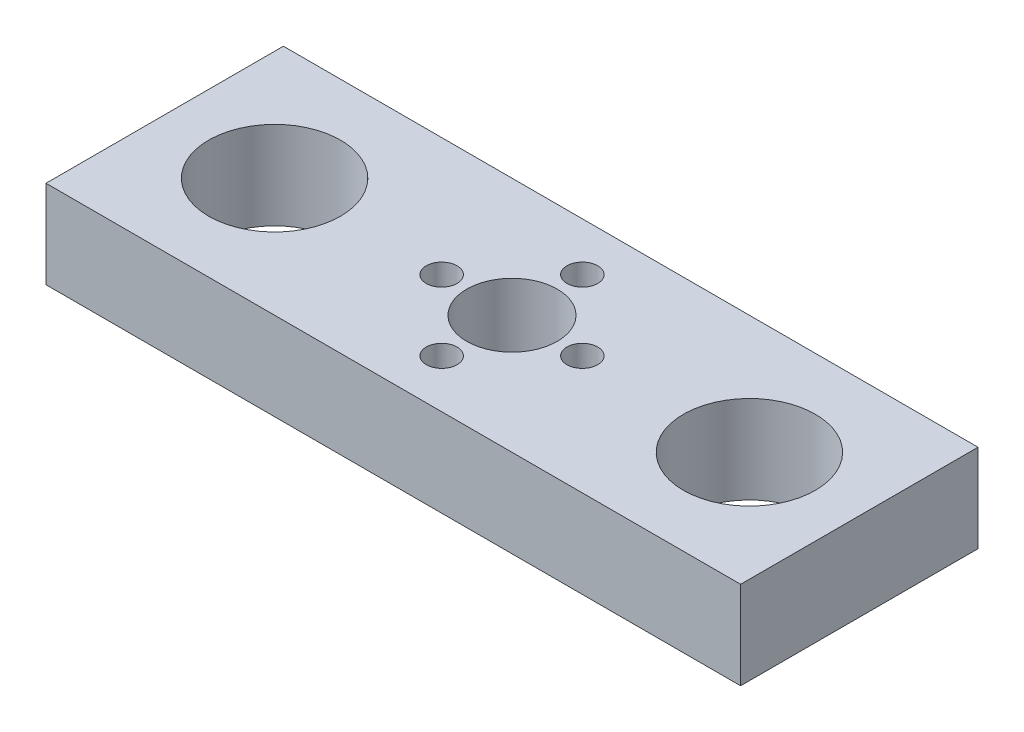
SolidWorks part; units mm, degrees
ref_plane "前视基准面" through (0, 0, 0) normal (0, 0, 1) x (1, 0, 0)
ref_plane "上视基准面" through (0, 0, 0) normal (0, 1, 0) x (1, 0, 0)
ref_plane "右视基准面" through (0, 0, 0) normal (1, 0, 0) x (0, 0, -1)
sketch "草图1" plane through (0, 0, 0) normal (0, 1, 0) x (1, 0, 0)
  line L1 (-39.5, 13.5) -> (39.5, 13.5)
  line L2 (-39.5, 13.5) -> (-39.5, -13.5)
  line L3 (-39.5, -13.5) -> (39.5, -13.5)
  line L4 (39.5, 13.5) -> (39.5, -13.5)
  line L5 (-39.5, 13.5) -> (39.5, -13.5) construction
  line L6 (-39.5, -13.5) -> (39.5, 13.5) construction
  point P0 (0, 0)
  dimension "D1" = 79
  dimension "D2" = 27
extrude "凸台-拉伸1" add sketch "草图1" along normal blind 10
sketch "草图2" plane through (0, 0, 0) normal (0, -1, 0) x (1, 0, 0)
  line L0 (-39.5, 0) -> (39.5, 0) construction
  line L1 (-39.5, -13.5) -> (-39.5, 13.5) construction
  line L2 (39.5, 13.5) -> (39.5, -13.5) construction
ref_plane "基准面1" through (0, 0, 0) normal (0, 0, 1) x (1, 0, 0)
sketch "草图3" plane through (0, 10, 0) normal (0, 1, 0) x (1, 0, 0)
  line L0 (-14.85, 0) -> (14.85, 0) construction
  line L1 (0, 13.5) -> (0, -13.5) construction
  line L2 (39.5, 13.5) -> (-39.5, 13.5) construction
  line L3 (-39.5, -13.5) -> (39.5, -13.5) construction
  circle A0 centre (-27, 0) radius 7.5
  circle A1 centre (27, 0) radius 7.5
  dimension "D1" = 15
  dimension "D2" = 54
extrude "切除-拉伸1" cut sketch "草图3" against normal through all contours A1 | A0
sketch "草图4" plane through (0, 10, 0) normal (0, 1, 0) x (1, 0, 0)
  circle A0 centre (0, 0) radius 5.15
  dimension "D1" = 10.3
extrude "切除-拉伸2" cut sketch "草图4" against normal through all
sketch "草图5" plane through (0, 10, 0) normal (0, 1, 0) x (1, 0, 0)
  circle A0 centre (8, 0) radius 1.75
  circle A1 centre (0, -8) radius 1.75
  circle A2 centre (-8, 0) radius 1.75
  circle A3 centre (0, 8) radius 1.75
  dimension "D1" = 3.5
extrude "切除-拉伸3" cut sketch "草图5" against normal through all
